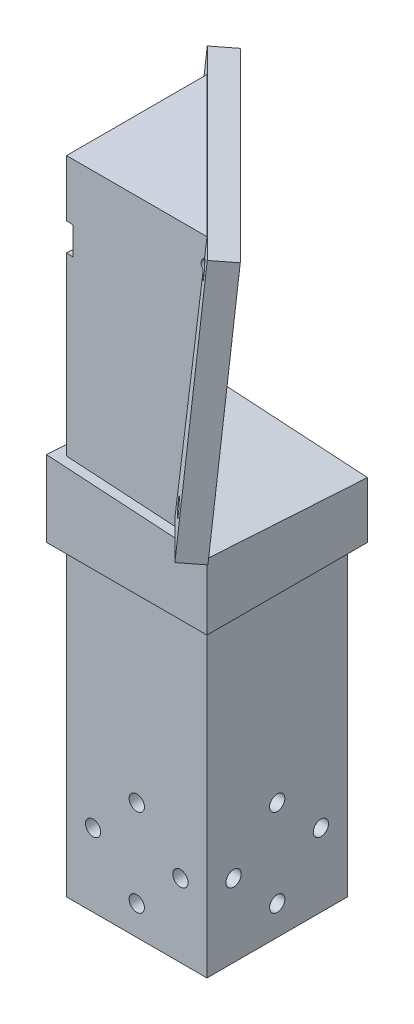
SolidWorks part; units mm, degrees
ref_plane "Front Plane" through (0, 0, 0) normal (0, 0, 1) x (1, 0, 0)
ref_plane "Top Plane" through (0, 0, 0) normal (0, 1, 0) x (1, 0, 0)
ref_plane "Right Plane" through (0, 0, 0) normal (1, 0, 0) x (0, 0, -1)
sketch "Sketch1" plane through (0, 0, 0) normal (0, 1, 0) x (1, 0, 0)
  line L1 (-15.2813, -15.2813) -> (15.2813, -15.2813)
  line L2 (-15.2813, -15.2813) -> (-15.2813, 15.2813)
  line L3 (-15.2813, 15.2813) -> (15.2813, 15.2813)
  line L4 (15.2813, -15.2813) -> (15.2813, 15.2813)
  line L5 (-15.2813, -15.2813) -> (15.2813, 15.2813) construction
  line L6 (-15.2813, 15.2813) -> (15.2813, -15.2813) construction
  point P0 (0, 0)
  point P5 (0, 0)
  dimension "D1" = 30.5626
extrude "Boss-Extrude1" add sketch "Sketch1" along normal blind 139.7 contours L1 L4 L3 L2
sketch "Sketch7" plane through (0, 139.7, 0) normal (0, 1, 0) x (1, 0, 0)
  line L0 (-15.2813, -15.2813) -> (15.2813, 15.2813) construction
ref_plane "Plane2" through (0, 0, 0) normal (-0.7071, 0, -0.7071) x (0, -1, 0)
sketch "Sketch2" plane through (0, 0, 0) normal (-0.7071, 0, -0.7071) x (0, -1, 0)
  line L2 (-139.7, 0) -> (-139.7, -21.611) construction
  line L4 (-139.7, -5.1193) -> (-81.186, 0)
  line L5 (-81.186, 0) -> (-79.2953, -21.611)
  line L8 (-139.7, -5.1193) -> (-139.7, -21.611)
  line L9 (-139.7, -21.611) -> (-79.2953, -21.611)
  line L10 (0, -21.611) -> (-139.7, -21.611) construction
  line L12 (0, 0) -> (-139.7, 0) construction
  dimension "D1" = 5
  dimension "D2" = 58.7375
extrude "Cut-Extrude1" cut sketch "Sketch2" against normal through all and the other way through all
sketch "Sketch4" plane through (-4.9843, 0.6167, 4.9843) normal (0.7044, -0.0872, -0.7044) x (-0.6991, 0.0864, -0.7098)
  line L0 (40.5773, 136.6098) -> (-16.3573, 141.5669)
  line L1 (-16.3573, 141.5669) -> (-21.3144, 84.6323)
  line L2 (-21.3144, 84.6323) -> (35.6202, 79.6752)
  line L3 (35.6202, 79.6752) -> (40.5773, 136.6098)
  line L4 (28.5395, 137.6579) -> (-4.3196, 140.5189) construction
  line L6 (11.9079, 136.7675) -> (12.2346, 140.5203) construction
  point P6 (12.11, 139.0884)
  dimension "D1" = 57.15
extrude "Boss-Extrude2" add sketch "Sketch4" against normal up to vertex (5.0998 mm away) up to point (15.2813, 139.7, 15.2813)
sketch "Sketch5" plane through (-4.9843, 0.6167, 4.9843) normal (0.7044, -0.0872, -0.7044) x (-0.6991, 0.0864, -0.7098)
  line L4 (19.8118, 123.7877) -> (9.8495, 124.6551)
  line L5 (9.8495, 124.6551) -> (9.3291, 118.6777)
  line L10 (35.6202, 79.6752) -> (40.5773, 136.6098) construction
  line L12 (40.5773, 136.6098) -> (-16.3573, 141.5669) construction
  line L13 (-10.8322, 134.9879) -> (30.095, 86.2543) construction
  line L14 (9.3291, 118.6777) -> (19.2914, 117.8103)
  line L19 (19.2914, 117.8103) -> (19.8118, 123.7877)
  line L21 (-10.8322, 134.9879) -> (33.9982, 131.0847) construction
  line L22 (33.9982, 131.0847) -> (30.095, 86.2543) construction
  line L23 (30.095, 86.2543) -> (-14.7354, 90.1575) construction
  line L24 (-14.7354, 90.1575) -> (-10.8322, 134.9879) construction
  line L25 (-5.5302, 97.8882) -> (22.3643, 95.4595) construction
  line L26 (-5.5302, 97.8882) -> (-3.1015, 125.7827) construction
  line L27 (-3.1015, 125.7827) -> (24.793, 123.354) construction
  line L28 (22.3643, 95.4595) -> (24.793, 123.354) construction
  line L29 (-5.5302, 97.8882) -> (24.793, 123.354) construction
  line L30 (-3.1015, 125.7827) -> (22.3643, 95.4595) construction
  line L31 (33.9982, 131.0847) -> (-14.7354, 90.1575) construction
  line L34 (-21.3144, 84.6323) -> (35.6202, 79.6752) construction
  line L35 (-21.3144, 84.6323) -> (-16.3573, 141.5669) construction
  line L36 (-16.3573, 141.5669) -> (40.5773, 136.6098) construction
  line L37 (35.6202, 79.6752) -> (40.5773, 136.6098) construction
  line L38 (-21.3144, 84.6323) -> (40.5773, 136.6098) construction
  line L39 (-16.3573, 141.5669) -> (35.6202, 79.6752) construction
  circle A4 centre (33.9982, 131.0847) radius 1.8
  circle A5 centre (-10.8322, 134.9879) radius 1.8
  circle A6 centre (-14.7354, 90.1575) radius 1.8
  circle A7 centre (30.095, 86.2543) radius 1.8
  point P6 (9.6314, 110.6211)
  point P15 (9.6314, 110.6211)
  point P25 (9.6314, 110.6211)
  dimension "D6" = 45
  dimension "D5" = 3.6
  dimension "D1" = 28
  dimension "D2" = 10
  dimension "D3" = 6
  dimension "D4" = 5
extrude "Cut-Extrude2" cut sketch "Sketch5" against normal through all
sketch "Sketch6" plane through (0, 0, 0) normal (1, 0, 0) x (0, 0, -1)
  line L0 (0, 25.4) -> (0, 6.4) construction
  line L1 (-9.5, 15.9) -> (9.5, 15.9) construction
  line L2 (-15.2813, 0) -> (15.2813, 0) construction
  circle A0 centre (0, 25.4) radius 1.6625
  circle A1 centre (-9.5, 15.9) radius 1.6625
  circle A2 centre (9.5, 15.9) radius 1.6625
  circle A3 centre (0, 6.4) radius 1.6625
  point P5 (0, 15.9)
  point P6 (0, 15.9)
  dimension "D3" = 3.325
  dimension "D1" = 19
  dimension "D2" = 25.4
extrude "Cut-Extrude3" cut sketch "Sketch6" against normal through all and the other way through all
mirror "Mirror1" about plane through (0, 0, 0) normal (-0.7071, 0, -0.7071) of "Cut-Extrude3"
sketch "Sketch8" plane through (0, 0, 0) normal (0, 1, 0) x (1, 0, 0)
  line L0 (15.2813, 15.2813) -> (-15.2813, 15.2813) construction
  line L1 (-17.4625, -17.4625) -> (17.4625, -17.4625)
  line L2 (-17.4625, -17.4625) -> (-17.4625, 17.4625)
  line L3 (-17.4625, 17.4625) -> (17.4625, 17.4625)
  line L4 (17.4625, -17.4625) -> (17.4625, 17.4625)
  line L5 (-17.4625, -17.4625) -> (17.4625, 17.4625) construction
  line L6 (-17.4625, 17.4625) -> (17.4625, -17.4625) construction
  line L7 (-15.2813, -15.2813) -> (15.2813, -15.2813)
  line L8 (-15.2813, -15.2813) -> (-15.2813, 15.2813)
  line L9 (-15.2813, 15.2813) -> (15.2813, 15.2813)
  line L10 (15.2813, -15.2813) -> (15.2813, 15.2813)
  line L11 (-15.2813, -15.2813) -> (15.2813, 15.2813) construction
  line L12 (-15.2813, 15.2813) -> (15.2813, -15.2813) construction
  point P0 (0, 0)
  point P5 (0, 0)
  dimension "D1" = 34.925
extrude "Boss-Extrude3" add sketch "Sketch8" along normal up to surface (16.5446 mm away) from offset 66.802
equation "\"tolerance\"= .2mm"
equation "\"id square tube\"= 1.375in - ( .078in * 2 )"
equation "\"angle down\"= 5deg"
equation "\"D1@Sketch1\"=\"id square tube\"-(2*\"tolerance\")"
equation "\"D3@Sketch6\"=\"tolerance\"+3.125mm"
equation "\"height\"= 5.5in"
equation "\"D1@Boss-Extrude1\"=\"height\""
equation "\"D1@Sketch2\"=\"angle down\""
